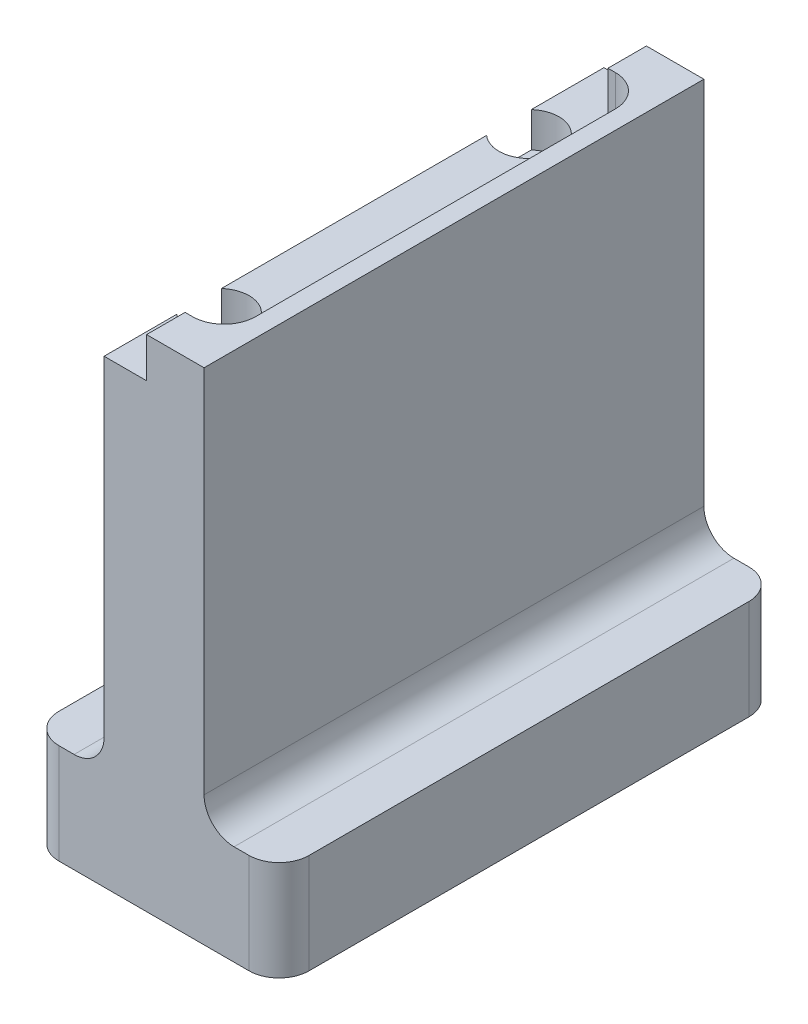
SolidWorks part; units mm, degrees
ref_plane "Alzado" through (0, 0, 0) normal (0, 0, 1) x (1, 0, 0)
ref_plane "Planta" through (0, 0, 0) normal (0, 1, 0) x (1, 0, 0)
ref_plane "Vista lateral" through (0, 0, 0) normal (1, 0, 0) x (0, 0, -1)
sketch "Croquis1" plane through (0, 0, 0) normal (0, 1, 0) x (1, 0, 0)
  line L1 (0, 0) -> (25, 0)
  line L2 (0, 0) -> (0, 50)
  line L3 (0, 50) -> (25, 50)
  line L4 (25, 0) -> (25, 50)
  dimension "D1" = 50
  dimension "D2" = 25
extrude "Saliente-Extruir1" add sketch "Croquis1" along normal blind 10
sketch "Croquis2" plane through (0, 10, 0) normal (0, 1, 0) x (1, 0, 0)
  line L0 (25, 50) -> (0, 50) construction
  line L1 (7.5, 50) -> (17.5, 50)
  line L2 (7.5, 50) -> (7.5, 0)
  line L3 (7.5, 0) -> (17.5, 0)
  line L4 (17.5, 50) -> (17.5, 0)
  line L5 (0, 0) -> (25, 0) construction
  line L6 (0, 50) -> (0, 0) construction
  dimension "D1" = 10
  dimension "D2" = 7.5
extrude "Saliente-Extruir2" add sketch "Croquis2" along normal blind 40
sketch "Croquis3" plane through (0, 50, 0) normal (0, 1, 0) x (1, 0, 0)
  line L0 (7.5, 50) -> (7.5, 0) construction
  line L1 (7.5, 46) -> (15.5, 46)
  line L2 (7.5, 46) -> (7.5, 4)
  line L3 (7.5, 4) -> (15.5, 4)
  line L4 (15.5, 46) -> (15.5, 4)
  line L5 (7.5, 0) -> (17.5, 0) construction
  dimension "D1" = 42
  dimension "D2" = 4
  dimension "D3" = 8
extrude "Cortar-Extruir1" cut sketch "Croquis3" against normal blind 4
fillet "Redondeo1" radius 3 2 edges at (15.5, 48, -4) (15.5, 48, -46)
sketch "Croquis4" plane through (0, 50, 0) normal (0, 1, 0) x (1, 0, 0)
  line L0 (7.5, 0) -> (17.5, 0) construction
  line L1 (7.5, 50) -> (11.6, 50)
  line L2 (7.5, 50) -> (7.5, 0)
  line L3 (7.5, 0) -> (11.6, 0)
  line L4 (11.6, 50) -> (11.6, 0)
  line L5 (17.5, 0) -> (17.5, 50) construction
  dimension "D1" = 5.9
extrude "Cortar-Extruir2" cut sketch "Croquis4" against normal up to surface (4 mm away) up to face at (12.0404, 46, -25)
sketch "Croquis5" plane through (0, 46, 0) normal (0, 1, 0) x (1, 0, 0)
  line L0 (11.6, 0) -> (7.5, 0) construction
  line L1 (7.5, 50) -> (11.6, 50) construction
  line L2 (17.5, 0) -> (17.5, 50) construction
  circle A0 centre (9.5, 9.5) radius 3
  circle A1 centre (9.5, 40.5) radius 3
  dimension "D1" = 6
  dimension "D2" = 9.5
  dimension "D3" = 9.5
  dimension "D4" = 8
extrude "Cortar-Extruir3" cut sketch "Croquis5" against normal blind 3.5
sketch "Croquis6" plane through (0, 50, 0) normal (0, 1, 0) x (1, 0, 0)
  line L0 (11.6, 4) -> (12.5, 4) construction
  line L1 (11.6, 50) -> (11.6, 46) construction
  line L2 (12.5, 46) -> (11.6, 46) construction
  line L3 (15.5, 7) -> (15.5, 43) construction
  line L4 (11.6, 0) -> (11.6, 4) construction
  line L5 (11.6, 4) -> (12.5, 4)
  line L6 (11.6, 0) -> (11.6, 4)
  line L7 (15.5, 7) -> (15.5, 43)
  line L8 (12.5, 46) -> (11.6, 46)
  line L9 (11.6, 50) -> (11.6, 46)
  line L10 (11.75, 0) -> (11.75, 3.85)
  line L11 (11.75, 3.85) -> (12.5, 3.85)
  line L12 (15.65, 7) -> (15.65, 43)
  line L13 (12.5, 46.15) -> (11.75, 46.15)
  line L14 (11.75, 50) -> (11.75, 46.15)
  line L15 (11.6, 50) -> (11.75, 50)
  line L16 (11.6, 0) -> (11.75, 0)
  arc A0 (15.5, 43) -> (12.5, 46) centre (12.5, 43) ccw construction
  arc A1 (12.5, 4) -> (15.5, 7) centre (12.5, 7) ccw construction
  arc A2 (12.5, 4) -> (15.5, 7) centre (12.5, 7) ccw
  arc A3 (15.5, 43) -> (12.5, 46) centre (12.5, 43) ccw
  arc A4 (12.5, 3.85) -> (15.65, 7) centre (12.5, 7) ccw
  arc A5 (15.65, 43) -> (12.5, 46.15) centre (12.5, 43) ccw
  dimension "D1" = 0.15
extrude "Cortar-Extruir4" cut sketch "Croquis6" against normal up to surface (4 mm away) up to face at (11.3316, 46, -25)
fillet "Redondeo2" radius 3 6 edges at (0, 5, -50) (25, 5, -50) (25, 5, 0) (0, 5, 0) (7.5, 10, -25) (17.5, 10, -25)
sketch "Croquis7" plane through (0, 0, 0) normal (0, -1, 0) x (1, 0, 0)
  line L0 (22, -50) -> (3, -50) construction
  line L1 (0, -47) -> (0, -3) construction
  circle A0 centre (-6, -25) radius 11.5
  dimension "D3" = 23
  dimension "D1" = 25
  dimension "D2" = 6
extrude "Cortar-Extruir5" cut sketch "Croquis7" against normal blind 15
